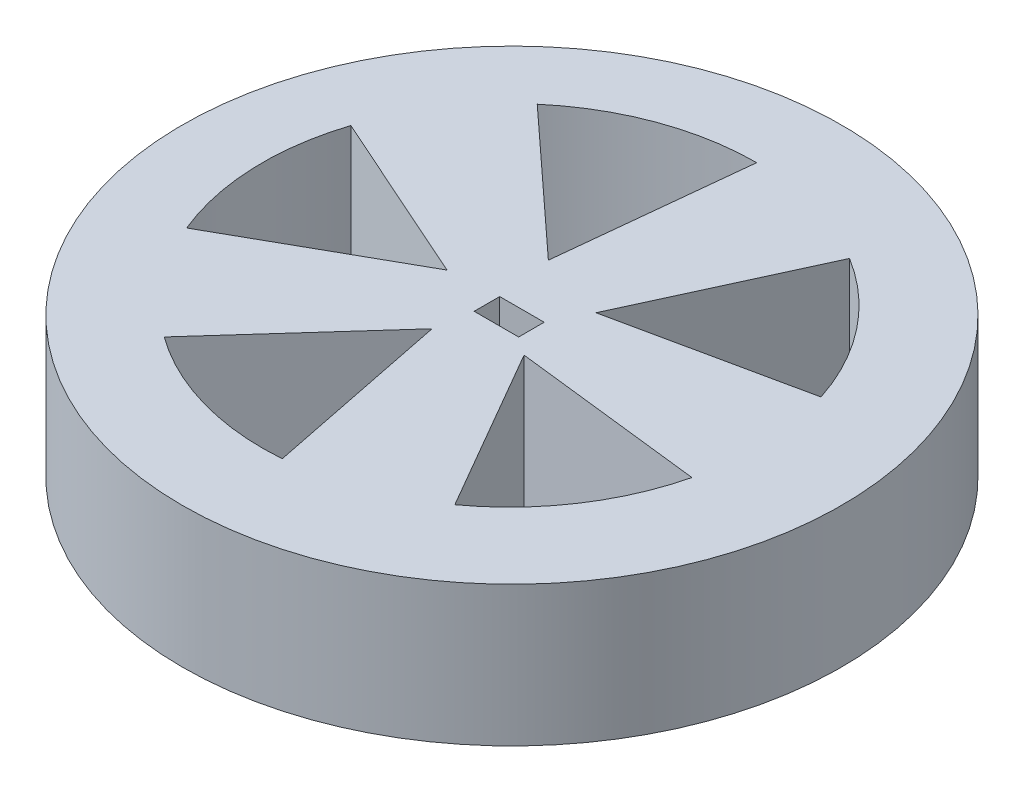
SolidWorks part; units mm, degrees
ref_plane "Plan de face" through (0, 0, 0) normal (0, 0, 1) x (1, 0, 0)
ref_plane "Plan de dessus" through (0, 0, 0) normal (0, 1, 0) x (1, 0, 0)
ref_plane "Plan de droite" through (0, 0, 0) normal (1, 0, 0) x (0, 0, -1)
sketch "Esquisse1" plane through (0, 0, 0) normal (0, 1, 0) x (1, 0, 0)
  circle A0 centre (1.176, -0.882) radius 40
  dimension "D1" = 80
extrude "Boss.-Extru.1" add sketch "Esquisse1" along normal blind 17
sketch "Esquisse4" plane through (0, 17, 0) normal (0, 1, 0) x (1, 0, 0)
  line L0 (-2.3912, 7.1086) -> (-19.4646, 22.8283)
  line L1 (-19.4646, 22.8283) -> (-2.3912, 7.1086)
  line L2 (-2.3912, 7.1086) -> (0, 30)
  line L3 (6.0218, 4.4708) -> (28.5317, 9.2705)
  line L4 (6.0218, 4.4708) -> (15.6961, 25.5662)
  line L5 (6.1128, -4.3455) -> (17.6336, -24.2705)
  line L6 (6.1128, -4.3455) -> (29.1653, -7.0275)
  line L7 (-2.2438, -7.1565) -> (-17.6336, -24.2705)
  line L8 (-2.2438, -7.1565) -> (2.329, -29.9095)
  line L9 (-7.4996, -0.0774) -> (-28.5317, 9.2705)
  line L10 (-7.4996, -0.0774) -> (-27.7259, -11.4576)
  circle A0 centre (0, 0) radius 30
  point P21 (0, 0)
  dimension "D1" = 60
  dimension "D3" = 5
extrude "Enlèv. mat.-Extru.1" cut sketch "Esquisse4" against normal blind 17 contours L2 A0 L0 | L3 A0 L4 | L5 A0 L6 | L7 A0 L8 | L9 A0 L10
sketch "Esquisse7" plane through (0, 0, 0) normal (0, -1, 0) x (-1, 0, 0)
  line L1 (1.5235, -2.7675) -> (-3.8765, -2.7675)
  line L2 (1.5235, -2.7675) -> (1.5235, 0.3325)
  line L3 (1.5235, 0.3325) -> (-3.8765, 0.3325)
  line L4 (-3.8765, -2.7675) -> (-3.8765, 0.3325)
  dimension "D1" = 3.1
  dimension "D2" = 5.4
extrude "Enlèv. mat.-Extru.3" cut sketch "Esquisse7" against normal blind 20 contours L2 L3 L4 L1
